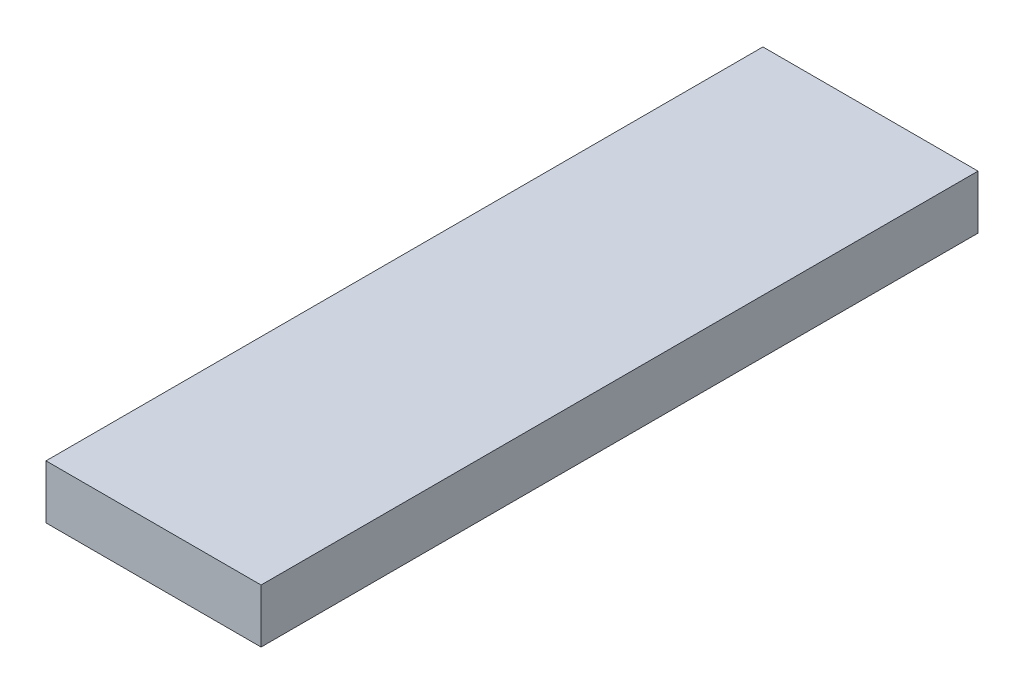
SolidWorks part; units mm, degrees
material "99.5% Aluminum Oxide (2)"
ref_plane "Front Plane" through (0, 0, 0) normal (0, 0, 1) x (1, 0, 0)
ref_plane "Top Plane" through (0, 0, 0) normal (0, 1, 0) x (1, 0, 0)
ref_plane "Right Plane" through (0, 0, 0) normal (1, 0, 0) x (0, 0, -1)
sketch "Sketch1" plane through (0, 0, 0) normal (0, 1, 0) x (1, 0, 0)
  line L1 (0, 50) -> (30, 50)
  line L2 (0, 50) -> (0, -50)
  line L3 (0, -50) -> (30, -50)
  line L4 (30, 50) -> (30, -50)
  dimension "D1" = 100
  dimension "D2" = 30
extrude "Boss-Extrude1" add sketch "Sketch1" along normal mid plane 7.5
ref_plane "Plane1" through (0, -3.25, 0) normal (0, -1, 0) x (-1, 0, 0)
ref_plane "Plane2" through (0, 3.25, 0) normal (0, 1, 0) x (1, 0, 0)
sketch "Sketch2" plane through (0, -3.25, 0) normal (0, 1, 0) x (1, 0, 0)
  line L0 (0, 25) -> (0, -25)
  line L1 (0, 50) -> (0, -50) construction
  line L2 (0, -25) -> (15, -25.2618)
  line L3 (15, -25.2618) -> (15, 25.2618)
  line L4 (15, 25.2618) -> (0, 25)
  line L5 (0, 0) -> (15, 0) construction
  dimension "D1" = 91
  dimension "D2" = 50
  dimension "D3" = 15
extrude "Cut-Extrude1" cut sketch "Sketch2" along normal up to surface (6.5 mm away)
